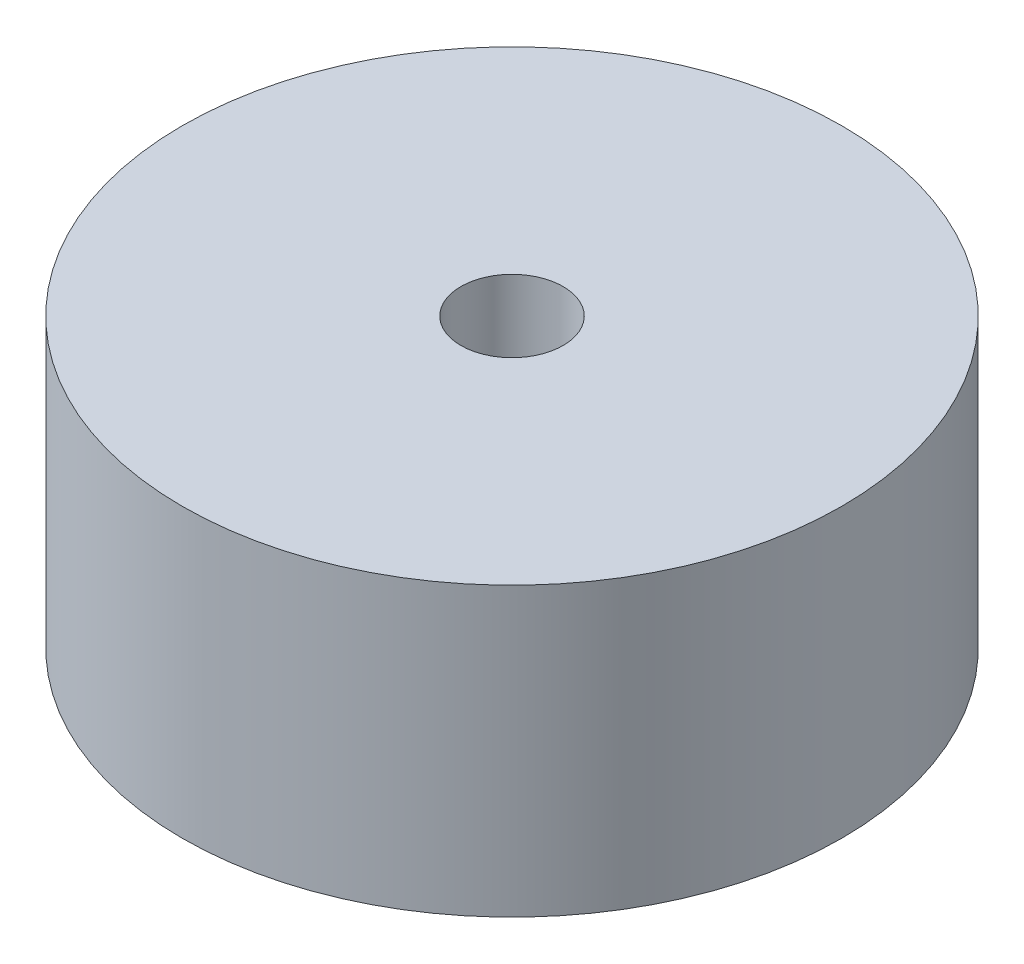
SolidWorks part; units mm, degrees
ref_plane "前视基准面" through (0, 0, 0) normal (0, 0, 1) x (1, 0, 0)
ref_plane "上视基准面" through (0, 0, 0) normal (0, 1, 0) x (1, 0, 0)
ref_plane "右视基准面" through (0, 0, 0) normal (1, 0, 0) x (0, 0, -1)
sketch "草图1" plane through (0, 0, 0) normal (0, 1, 0) x (1, 0, 0)
  circle A0 centre (0, 0) radius 57.34
extrude "凸台-拉伸2" add sketch "草图1" along normal blind 50
sketch "草图3" plane through (0, 50, 0) normal (0, 1, 0) x (1, 0, 0)
  circle A0 centre (0, 0) radius 8.89
extrude "切除-拉伸1" cut sketch "草图3" against normal blind 50
